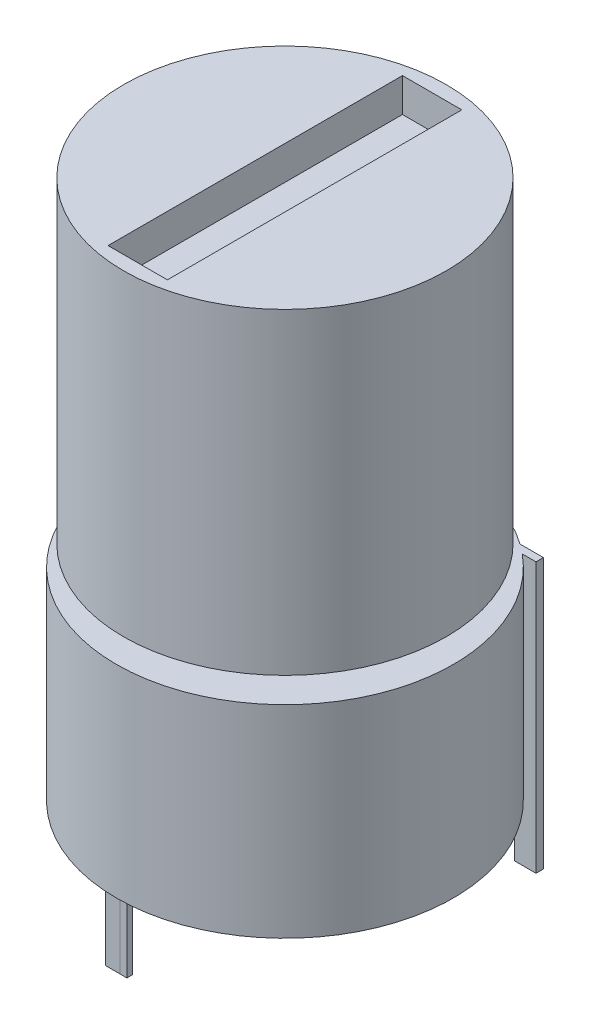
SolidWorks part; units mm, degrees
ref_plane "前视基准面" through (0, 0, 0) normal (0, 0, 1) x (1, 0, 0)
ref_plane "上视基准面" through (0, 0, 0) normal (0, 1, 0) x (1, 0, 0)
ref_plane "右视基准面" through (0, 0, 0) normal (1, 0, 0) x (0, 0, -1)
sketch "草图1" plane through (0, 0, 0) normal (0, 1, 0) x (1, 0, 0)
  circle A0 centre (0, 0) radius 2.5
extrude "凸台-拉伸1" add sketch "草图1" along normal blind 3 contours A0
sketch "草图2" plane through (0, 3, 0) normal (0, 1, 0) x (1, 0, 0)
  circle A0 centre (0, 0) radius 0.188
extrude "凸台-拉伸2" add sketch "草图2" along normal blind 7.3
sketch "草图4" plane through (0, 10.3, 0) normal (0, 1, 0) x (1, 0, 0)
  circle A0 centre (0, 0) radius 0.188
extrude "切除-拉伸1" cut sketch "草图4" against normal blind 2.3
sketch "草图6" plane through (0, 8, 0) normal (0, 1, 0) x (1, 0, 0)
  circle A1 centre (0, 0) radius 2.3921
extrude "凸台-拉伸3" add sketch "草图6" against normal blind 4.7
sketch "草图7" plane through (0, 8, 0) normal (0, 1, 0) x (1, 0, 0)
  line L1 (-0.44, -2.183) -> (0.44, -2.183)
  line L2 (-0.44, -2.183) -> (-0.44, 2.183)
  line L3 (-0.44, 2.183) -> (0.44, 2.183)
  line L4 (0.44, -2.183) -> (0.44, 2.183)
  line L5 (-0.44, -2.183) -> (0.44, 2.183) construction
  line L6 (-0.44, 2.183) -> (0.44, -2.183) construction
  point P0 (0, 0)
extrude "切除-拉伸3" cut sketch "草图7" against normal blind 0.5
sketch "草图9" plane through (0, 0, 0) normal (0, -1, 0) x (1, 0, 0)
  line L0 (0, 2.4481) -> (0.4735, 2.4547)
  line L1 (0.4735, 2.4547) -> (0.4735, 2.3625)
  line L2 (0.4735, 2.3625) -> (-0.5069, 2.3625)
  line L3 (0, 2.4481) -> (-0.5069, 2.4481)
  line L4 (-0.5069, 2.4481) -> (-0.5069, 2.3625)
  circle A1 centre (0, 0) radius 2.5 construction
extrude "凸台-拉伸4" add sketch "草图9" along normal blind 1
sketch "草图10" plane through (0, 3, 0) normal (0, 1, 0) x (1, 0, 0)
  line L0 (-1.4577, 1.9286) -> (-1.7671, 1.9286)
  line L1 (-1.7671, 1.9286) -> (-1.7671, 2.0386)
  line L2 (-1.7671, 2.0386) -> (-1.447, 2.0386)
  line L3 (-1.447, 2.0386) -> (-1.4577, 1.9286)
  line L4 (1.4783, 1.9286) -> (1.447, 2.0386)
  line L5 (1.447, 2.0386) -> (1.7946, 2.0386)
  line L6 (1.7946, 2.0386) -> (1.7946, 1.9286)
  line L7 (1.7946, 1.9286) -> (1.4783, 1.9286)
  circle A0 centre (0, 0) radius 2.5 construction
extrude "凸台-拉伸5" add sketch "草图10" against normal blind 4
sketch "草图11" plane through (0, -1, 0) normal (0, -1, 0) x (1, 0, 0)
  line L0 (0, 2.4481) -> (-0.5069, 2.4481) construction
  line L1 (-0.2159, 2.4481) -> (-0.2159, 2.3625)
  line L2 (-0.5069, 2.3625) -> (0.4735, 2.3625) construction
  line L3 (-0.2159, 2.3625) -> (-0.5069, 2.3625)
  line L4 (-0.5069, 2.3625) -> (-0.5069, 2.4481)
  line L5 (-0.5069, 2.4481) -> (-0.2159, 2.4481)
  line L6 (0.1051, 2.4496) -> (0.1051, 2.3625)
  line L7 (0.4735, 2.4547) -> (0, 2.4481) construction
  line L8 (-0.5069, 2.3625) -> (0.4735, 2.3625) construction
  line L9 (0.1051, 2.3625) -> (0.4735, 2.3625)
  line L10 (0.4735, 2.3625) -> (0.4735, 2.4547)
  line L11 (0.4735, 2.4547) -> (0.1051, 2.4496)
extrude "切除-拉伸4" cut sketch "草图11" against normal blind 1
